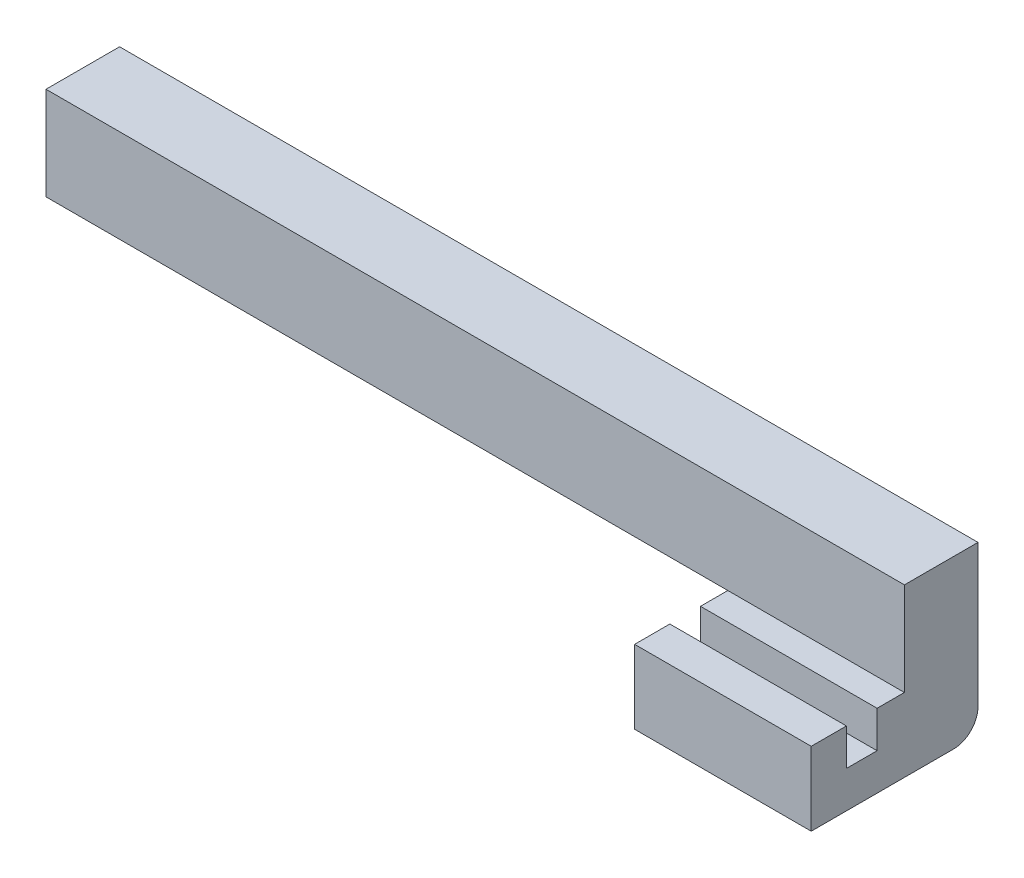
SolidWorks part; units mm, degrees
ref_plane "Ebene vorne" through (0, 0, 0) normal (0, 0, 1) x (1, 0, 0)
ref_plane "Ebene oben" through (0, 0, 0) normal (0, 1, 0) x (1, 0, 0)
ref_plane "Ebene rechts" through (0, 0, 0) normal (1, 0, 0) x (0, 0, -1)
sketch "Sketch1" plane through (0, 0, 0) normal (0, 1, 0) x (1, 0, 0)
  line L1 (-3.6, 1.9) -> (3.6, 1.9)
  line L2 (-3.6, 1.9) -> (-3.6, -1.9)
  line L3 (-3.6, -1.9) -> (3.6, -1.9)
  line L4 (3.6, 1.9) -> (3.6, -1.9)
  line L5 (-3.6, 1.9) -> (3.6, -1.9) construction
  line L6 (-3.6, -1.9) -> (3.6, 1.9) construction
  line L7 (-1.6, 0.7856) -> (1.6, 0.7856)
  line L8 (-1.6, 0.7856) -> (-1.6, -0.4644)
  line L9 (-1.6, -0.4644) -> (1.6, -0.4644)
  line L10 (1.6, 0.7856) -> (1.6, -0.4644)
  line L11 (-1.6, 0.7856) -> (1.6, -0.4644) construction
  line L12 (-1.6, -0.4644) -> (1.6, 0.7856) construction
  point P0 (0, 0)
  point P6 (0, 0.1606)
  dimension "D1" = 3.8
  dimension "D2" = 7.2
  dimension "D3" = 2
  dimension "D4" = 1.25
  dimension "D5" = 3.2
extrude "Boss-Extrude1" add sketch "Sketch1" along normal blind 3
sketch "Sketch6" plane through (0, 3, 0) normal (0, 1, 0) x (1, 0, 0)
  line L0 (1.6, 0.7856) -> (-1.6, 0.7856) construction
  line L1 (-5.5, 0.7856) -> (7.5, 0.7856)
  line L2 (-5.5, 0.7856) -> (-5.5, -0.4644)
  line L3 (-5.5, -0.4644) -> (7.5, -0.4644)
  line L4 (7.5, 0.7856) -> (7.5, -0.4644)
  line L5 (-1.6, -0.4644) -> (1.6, -0.4644) construction
  line L7 (1.6, -0.4644) -> (-1.6, 0.7856) construction
  point P12 (0, 0.1606)
  dimension "D1" = 5.5
  dimension "D2" = 7.5
extrude "Cut-Extrude2" cut sketch "Sketch6" against normal blind 1.5
sketch "Sketch7" plane through (0, 0, -1.9) normal (0, 0, -1) x (-1, 0, 0)
  line L0 (-3.6, 3) -> (3.6, 3) construction
  line L1 (-3.6, 0) -> (3.6, 0)
  line L2 (-3.6, 0) -> (-3.6, 6.8)
  line L3 (-3.6, 6.8) -> (31.4, 6.8)
  line L4 (31.4, 3) -> (31.4, 6.8)
  line L5 (3.6, 3) -> (31.4, 3)
  line L6 (3.6, 3) -> (3.6, 0)
  line L7 (3.6, 3) -> (3.6, 0) construction
  dimension "D1" = 3.8
  dimension "D2" = 35
extrude "Boss-Extrude2" add sketch "Sketch7" along normal blind 3
fillet "Fillet1" radius 1 1 edges at (0, 0, -4.9)
